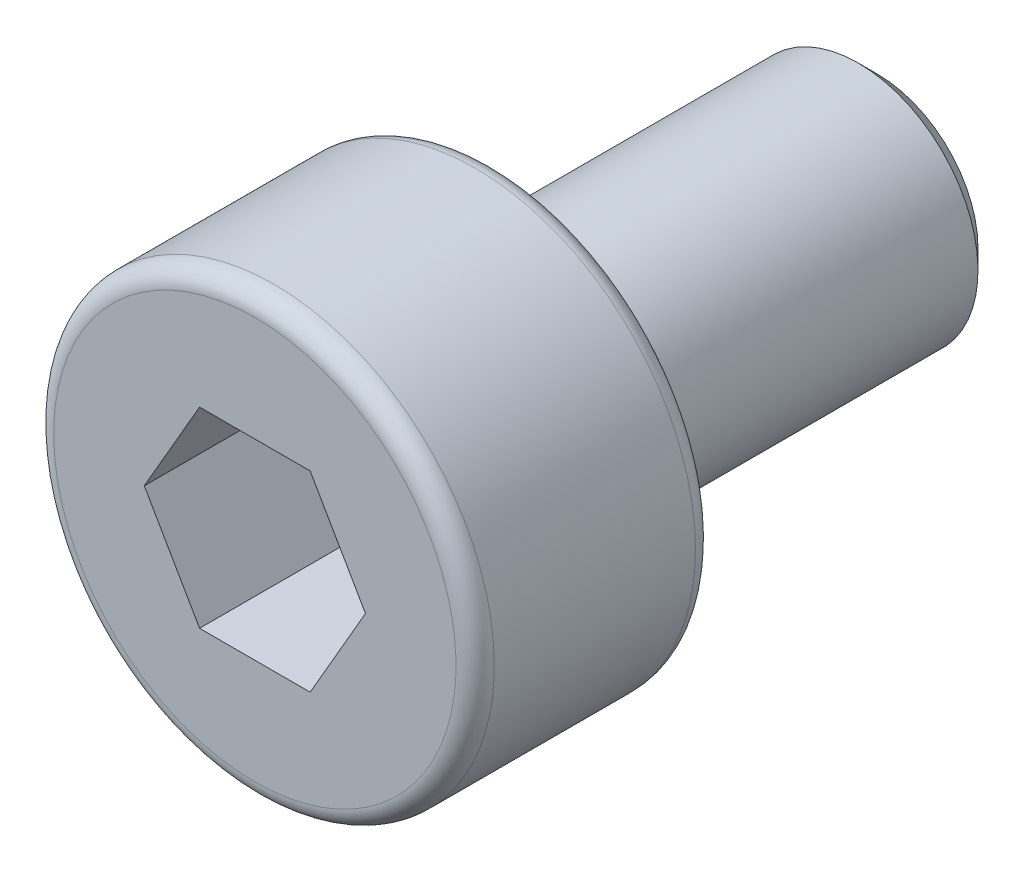
SolidWorks part; units mm, degrees
ref_plane "前视基准面" through (0, 0, 0) normal (0, 0, 1) x (1, 0, 0)
ref_plane "上视基准面" through (0, 0, 0) normal (0, 1, 0) x (1, 0, 0)
ref_plane "右视基准面" through (0, 0, 0) normal (1, 0, 0) x (0, 0, -1)
sketch "草图2" plane through (0, 0, 0) normal (1, 0, 0) x (0, 0, -1)
  line L0 (0, 0) -> (0, 2.3)
  line L1 (0, 2.3) -> (2.5, 2.3)
  line L2 (2.5, 2.3) -> (2.5, 1.25)
  line L3 (2.5, 1.25) -> (6.5, 1.25)
  line L5 (6.5, 1.25) -> (6.5, 0)
  line L6 (6.5, 0) -> (0, 0)
  dimension "D1" = 1.25
  dimension "D2" = 2.3
  dimension "D3" = 2.5
  dimension "D4" = 4
revolve "旋转1" add sketch "草图2" angle 360 about L6
fillet "圆角1" radius 0.2 2 edges at (0, 2.3, -2.5) (0, 2.3, 0)
chamfer "倒角1" distance 0.2 angle 45 1 edges at (0, 1.25, -6.5)
sketch "草图3" plane through (0, 0, 0) normal (0, 0, 1) x (1, 0, 0)
  line L1 (1.1547, 0) -> (0.5774, 1)
  line L2 (0.5774, 1) -> (-0.5774, 1)
  line L3 (-0.5774, 1) -> (-1.1547, 0)
  line L4 (-1.1547, 0) -> (-0.5774, -1)
  line L5 (-0.5774, -1) -> (0.5774, -1)
  line L6 (0.5774, -1) -> (1.1547, 0)
  circle A0 centre (0, 0) radius 1 construction
  dimension "D1" = 2
extrude "切除-拉伸1" cut sketch "草图3" against normal blind 1.5
